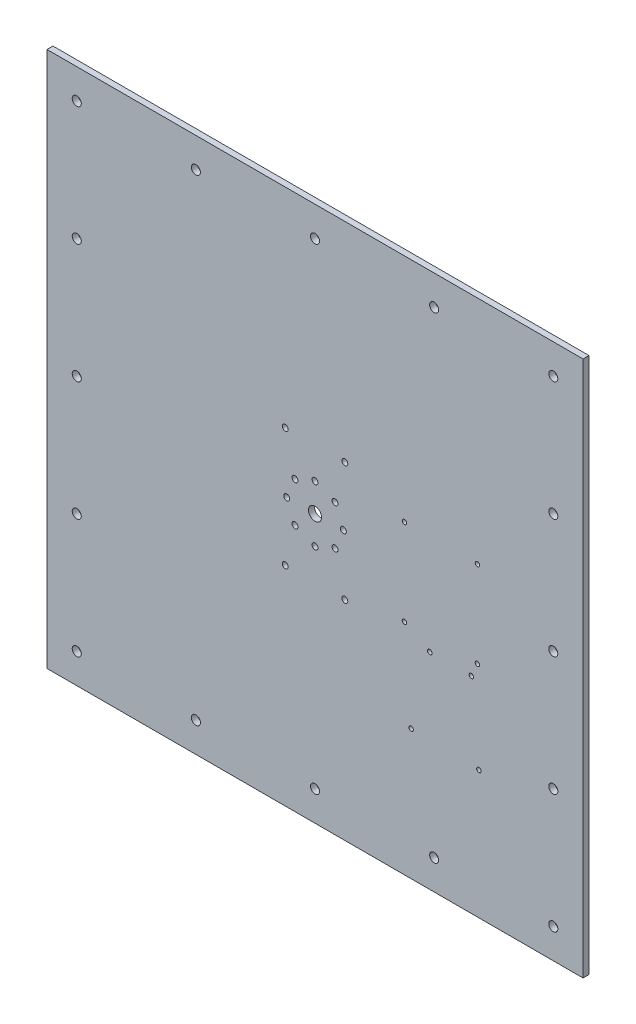
SolidWorks part; units mm, degrees
ref_plane "前视基准面" through (0, 0, 0) normal (0, 0, 1) x (1, 0, 0)
ref_plane "上视基准面" through (0, 0, 0) normal (0, 1, 0) x (1, 0, 0)
ref_plane "右视基准面" through (0, 0, 0) normal (1, 0, 0) x (0, 0, -1)
sketch "草图1" plane through (0, 0, 0) normal (0, 0, 1) x (1, 0, 0)
  line L0 (0, 19.5563) -> (0, -0.4437) construction
  line L1 (0, -0.4437) -> (-40, -0.4437) construction
  line L2 (0, 19.5563) -> (0, 85.5563) construction
  line L3 (-40, 39.5563) -> (-40, -0.4437) construction
  line L4 (-40, -0.4437) -> (-40, -40.4437) construction
  line L5 (-40, 39.5563) -> (0, 39.5563) construction
  line L6 (-20, -0.4437) -> (-20, 39.5563) construction
  line L7 (-100, 79.5563) -> (60, 79.5563) construction
  line L8 (-100, 79.5563) -> (-100, -80.4437) construction
  line L9 (-100, -80.4437) -> (60, -80.4437) construction
  line L10 (60, 79.5563) -> (60, -80.4437) construction
  line L11 (-100, 79.5563) -> (-100, 179.5563) construction
  line L12 (-200, 179.5563) -> (160, 179.5563)
  line L13 (-200, 179.5563) -> (-200, -180.4437)
  line L14 (-200, -180.4437) -> (160, -180.4437)
  line L15 (160, 179.5563) -> (160, -180.4437)
  line L16 (-100, -80.4437) -> (-200, -80.4437) construction
  line L17 (-100, -80.4437) -> (-100, -180.4437) construction
  line L18 (60, 79.5563) -> (160, 79.5563) construction
  circle A0 centre (0, 19.5563) radius 10 construction
  circle A2 centre (-40, -0.4437) radius 2 construction
  circle A3 centre (-40, 39.5563) radius 2
  circle A4 centre (0, 39.5563) radius 2
  circle A5 centre (0, -0.4437) radius 2 construction
  circle A6 centre (0, -40.4437) radius 2
  circle A7 centre (-40, -40.4437) radius 2
  circle A8 centre (-20, -0.4437) radius 4.4
  dimension "D2" = 4
  dimension "D11" = 100
  dimension "D3" = 40
  dimension "D4" = 40
  dimension "D5" = 40
  dimension "D6" = 40
  dimension "D7" = 60
  dimension "D8" = 80
  dimension "D9" = 80
  dimension "D10" = 80
extrude "凸台-拉伸1" add sketch "草图1" along normal blind 4
sketch "草图2" plane through (0, 0, 4) normal (0, 0, 1) x (1, 0, 0)
  line L0 (39.2612, -39.8138) -> (92.5612, -39.8138) construction
  line L1 (39.2612, -39.8138) -> (39.2612, -108.4138) construction
  line L2 (39.2612, -108.4138) -> (92.5612, -108.4138) construction
  line L3 (92.5612, -39.8138) -> (92.5612, -108.4138) construction
  line L4 (40.0612, 24.7685) -> (40.0612, -33.2315) construction
  line L5 (40.0612, 24.7685) -> (89.0612, 24.7685) construction
  line L6 (89.0612, 24.7685) -> (89.0612, -33.2315) construction
  line L7 (40.0612, -33.2315) -> (36.5612, -33.2315)
  line L8 (36.5612, 48.2685) -> (92.5612, 48.2685) construction
  line L9 (36.5612, 48.2685) -> (36.5612, -36.7315) construction
  line L10 (36.5612, -36.7315) -> (92.5612, -36.7315) construction
  line L11 (92.5612, 48.2685) -> (92.5612, -36.7315) construction
  line L12 (89.0612, -33.2315) -> (92.5612, -33.2315) construction
  circle A0 centre (57.0612, -42.3138) radius 1.5
  circle A1 centre (84.9612, -42.3138) radius 1.5
  circle A2 centre (44.5612, -93.1138) radius 1.5
  circle A3 centre (90.0612, -94.4138) radius 1.5
  circle A4 centre (40.0612, 24.7685) radius 1.5
  circle A5 centre (89.0612, 24.7685) radius 1.5
  circle A6 centre (40.0612, -33.2315) radius 1.5
  circle A7 centre (89.0612, -33.2315) radius 1.5
  dimension "D1" = 3
  dimension "D2" = 58
  dimension "D3" = 49
  dimension "D4" = 85
  dimension "D5" = 56
  dimension "D6" = 3.5
extrude "切除-拉伸2" cut sketch "草图2" against normal blind 20 contours A2 | A3 | A0 | A1 | A6 | A7 | A5 | A4
sketch "草图3" plane through (0, 0, 4) normal (0, 0, 1) x (1, 0, 0)
  line L0 (-200, 179.5563) -> (-200, -180.4437) construction
  line L1 (-180, 159.5563) -> (140, 159.5563) construction
  line L2 (-180, 159.5563) -> (-180, -160.4437) construction
  line L3 (-180, -160.4437) -> (140, -160.4437) construction
  line L4 (140, 159.5563) -> (140, -160.4437) construction
  line L5 (-180, 159.5563) -> (-200, 159.5563) construction
  line L6 (-180, 159.5563) -> (-180, 179.5563) construction
  line L7 (160, 179.5563) -> (-200, 179.5563) construction
  line L8 (-180, -160.4437) -> (-180, -180.4437) construction
  line L9 (-200, -180.4437) -> (160, -180.4437) construction
  line L10 (140, -160.4437) -> (160, -160.4437) construction
  line L11 (160, -180.4437) -> (160, 179.5563) construction
  circle A1 centre (-180, -160.4437) radius 3.04
  circle A2 centre (-180, -80.4437) radius 3.04
  circle A3 centre (-180, -0.4437) radius 3.04
  circle A4 centre (-180, 79.5563) radius 3.04
  circle A5 centre (-180, 159.5563) radius 3.04
  circle A6 centre (-100, 159.5563) radius 3.04
  circle A7 centre (-20, 159.5563) radius 3.04
  circle A8 centre (60, 159.5563) radius 3.04
  circle A9 centre (140, 159.5563) radius 3.04
  circle A10 centre (140, 79.5563) radius 3.04
  circle A11 centre (140, -0.4437) radius 3.04
  circle A12 centre (140, -80.4437) radius 3.04
  circle A13 centre (140, -160.4437) radius 3.04
  circle A14 centre (60, -160.4437) radius 3.04
  circle A15 centre (-20, -160.4437) radius 3.04
  circle A16 centre (-100, -160.4437) radius 3.04
  dimension "D2" = 6.08
  dimension "D1" = 20
  dimension "D3" = 4
  dimension "D4" = 4
extrude "切除-拉伸3" cut sketch "草图3" against normal blind 20
sketch "草图4" plane through (0, 0, 4) normal (0, 0, 1) x (1, 0, 0)
  circle A0 centre (-20, -0.4437) radius 19 construction
  circle A1 centre (-20, -19.4437) radius 2
  circle A2 centre (-33.435, -13.8788) radius 2
  circle A3 centre (-39, -0.4437) radius 2
  circle A4 centre (-33.435, 12.9913) radius 2
  circle A5 centre (-20, 18.5563) radius 2
  circle A6 centre (-6.565, 12.9913) radius 2
  circle A7 centre (-1, -0.4437) radius 2
  circle A8 centre (-6.565, -13.8788) radius 2
  dimension "D1" = 38
  dimension "D2" = 4
  dimension "D3" = 8
extrude "切除-拉伸4" cut sketch "草图4" against normal blind 10
